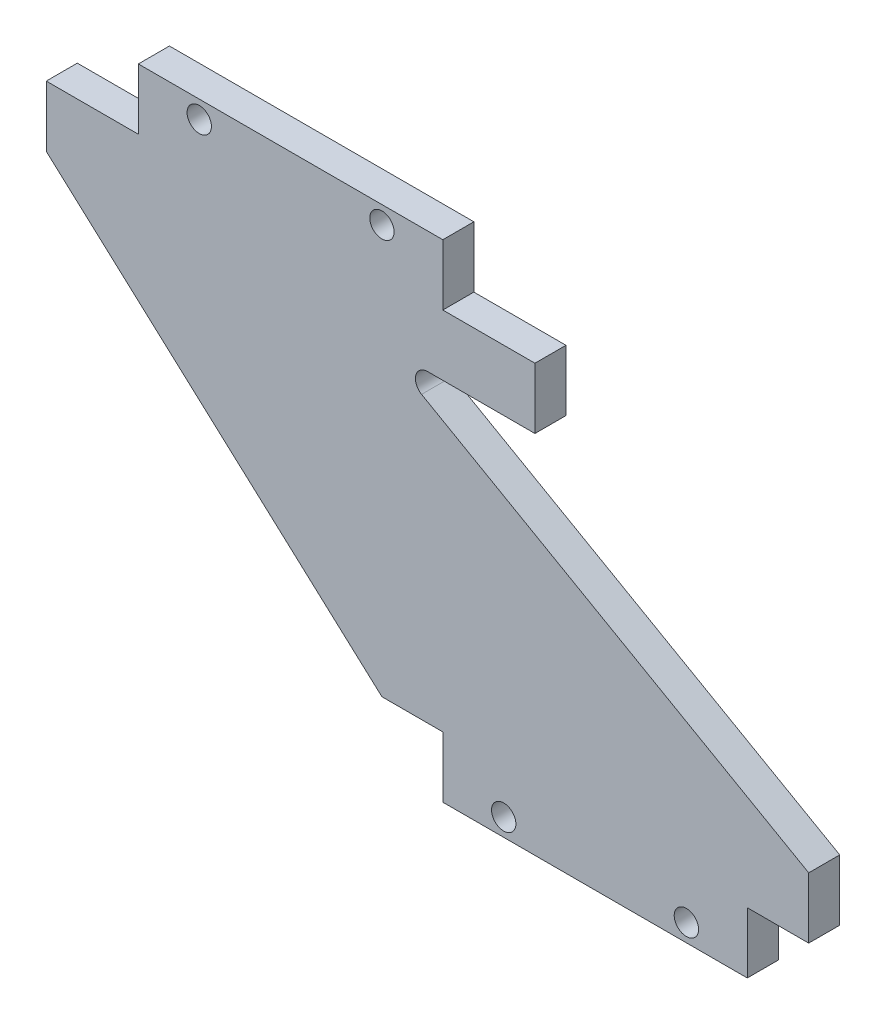
SolidWorks part; units mm, degrees
ref_plane "Front Plane" through (0, 0, 0) normal (0, 0, 1) x (1, 0, 0)
ref_plane "Top Plane" through (0, 0, 0) normal (0, 1, 0) x (1, 0, 0)
ref_plane "Right Plane" through (0, 0, 0) normal (1, 0, 0) x (0, 0, -1)
sketch "Sketch1" plane through (0, 0, 0) normal (0, 0, 1) x (1, 0, 0)
  line L0 (-42.4843, 62.1016) -> (-42.4843, 52.1016)
  line L1 (-42.4843, 52.1016) -> (-57.6105, 52.1016)
  line L2 (-57.6105, 52.1016) -> (-57.6105, 42.1016)
  line L3 (-57.6105, 42.1016) -> (-2.4843, -7.8984)
  line L4 (-2.4843, -7.8984) -> (7.5157, -7.8984)
  line L5 (7.5157, -7.8984) -> (7.5157, -17.8984)
  line L6 (7.5157, -17.8984) -> (57.5157, -17.8984)
  line L7 (57.5157, -17.8984) -> (57.5157, -7.8984)
  line L8 (57.5157, -7.8984) -> (67.5999, -7.8984)
  line L9 (67.5999, -7.8984) -> (67.5999, 2.1016)
  line L10 (67.5999, 2.1016) -> (4.0228, 38.3643)
  line L11 (5.0137, 42.1016) -> (22.642, 42.1016)
  line L12 (22.642, 42.1016) -> (22.642, 52.1016)
  line L13 (22.642, 52.1016) -> (7.5157, 52.1016)
  line L14 (7.5157, 52.1016) -> (7.5157, 62.1016)
  line L15 (7.5157, 62.1016) -> (-42.4843, 62.1016)
  arc A0 (5.0137, 42.1016) -> (4.0228, 38.3643) centre (5.0137, 40.1016) ccw
  circle A1 centre (-32.4843, 59.2016) radius 2
  circle A2 centre (-2.4843, 59.2016) radius 2
  circle A3 centre (17.5157, -14.9984) radius 2
  circle A4 centre (47.5157, -14.9984) radius 2
  point P26 (0, 0)
  point P27 (0, 0)
  point P28 (3.0813, -14.452)
  point P29 (4.4755, -13.5432)
  point P30 (4.0624, -15.1957)
  dimension "D1" = 2
  dimension "D12" = 4
  dimension "D13" = 2.9
  dimension "D2" = 10
  dimension "D3" = 10
  dimension "D4" = 10
  dimension "D5" = 10
  dimension "D6" = 10
  dimension "D7" = 10
  dimension "D8" = 10
  dimension "D9" = 60
  dimension "D10" = 50
  dimension "D11" = 50
  dimension "D14" = 10
  dimension "D15" = 10
  dimension "D16" = 2.9
  dimension "D17" = 10
  dimension "D18" = 50
  dimension "10" = 10
  dimension "D19" = 10
extrude "Boss-Extrude1" add sketch "Sketch1" along normal blind 5.1
